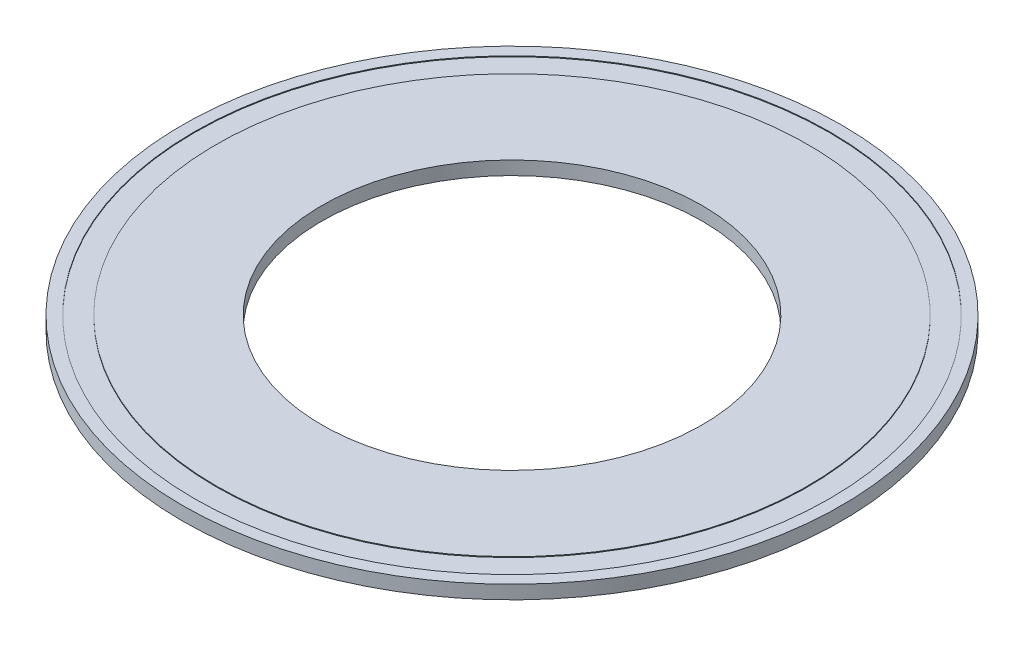
SolidWorks part; units mm, degrees
material "Verre"
ref_plane "Plan de face" through (0, 0, 0) normal (0, 0, 1) x (1, 0, 0)
ref_plane "Plan de dessus" through (0, 0, 0) normal (0, 1, 0) x (1, 0, 0)
ref_plane "Plan de droite" through (0, 0, 0) normal (1, 0, 0) x (0, 0, -1)
sketch "Esquisse1" plane through (0, 0, 0) normal (0, 0, 1) x (1, 0, 0)
  line L0 (22.5, -0.8) -> (39, -0.8)
  line L1 (39, -0.8) -> (39, 0.8)
  line L2 (0, 0) -> (61.3075, 0) construction
  line L5 (22.5, -21.8) -> (22.5, 0.3) construction
  line L6 (39, 0.8) -> (22.5, 0.8)
  line L7 (22.5, 0.8) -> (22.5, -0.8)
  line L8 (0, -15.2986) -> (0, 54.0773) construction
  dimension "D1" = 1.6
  dimension "D3" = 78
revolve "Révolution1" add sketch "Esquisse1" angle 360 about L8
sketch "Esquisse2" plane through (0, 0.8, 0) normal (0, 1, 0) x (1, 0, 0)
  circle A0 centre (0, 0) radius 37.6
  circle A1 centre (0, 0) radius 35
  dimension "D1" = 75.2
  dimension "D2" = 70
extrude "Enlèv. mat.-Extru.1" cut sketch "Esquisse2" against normal blind 0.1
